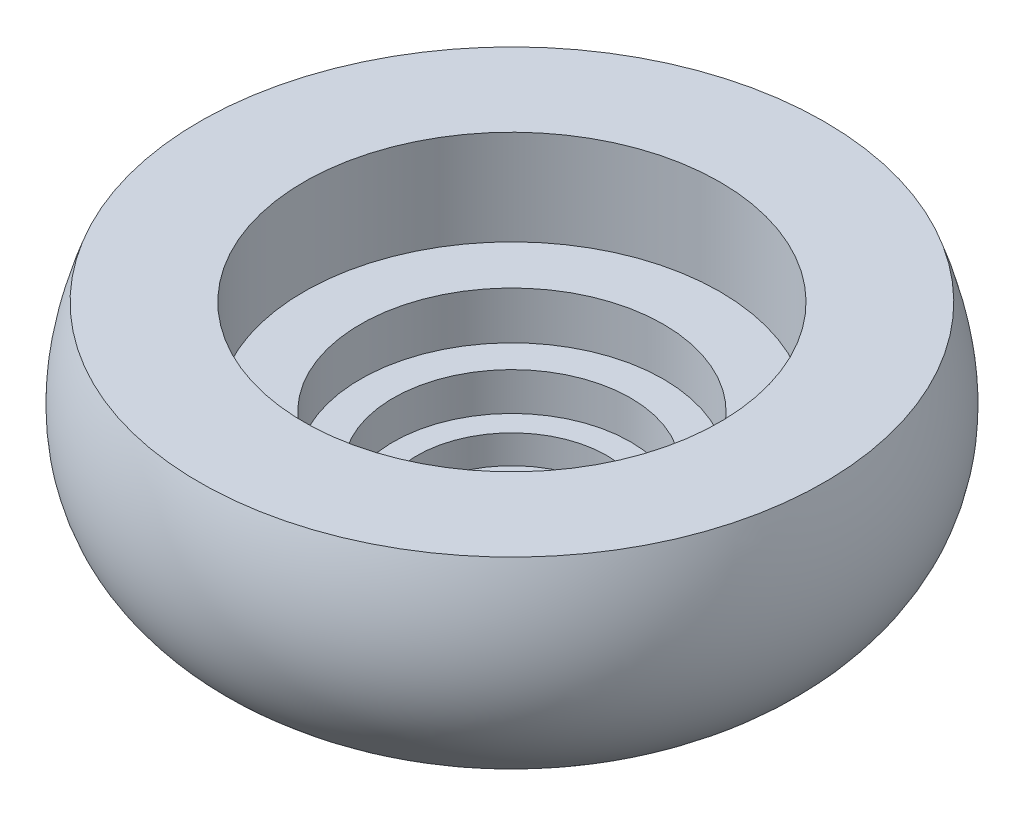
SolidWorks part; units mm, degrees
ref_plane "정면" through (0, 0, 0) normal (0, 0, 1) x (1, 0, 0)
ref_plane "윗면" through (0, 0, 0) normal (0, 1, 0) x (1, 0, 0)
ref_plane "우측면" through (0, 0, 0) normal (1, 0, 0) x (0, 0, -1)
sketch "스케치2" plane through (0, 0, 0) normal (0, 0, 1) x (1, 0, 0)
  line L0 (0, 0) -> (39.9375, 0) construction
  line L1 (39.9375, 0) -> (-43.125, 0) construction
  line L2 (0, 0) -> (0, 23.4063) construction
  line L3 (0, 23.4063) -> (0, -23.2813) construction
  line L4 (0, 0) -> (-5, 0)
  line L5 (-21.9, 30) -> (-32.9, 30)
  line L6 (-21.9, 30) -> (-21.9, 20)
  line L7 (-21.9, 20) -> (-15.95, 20)
  line L8 (-15.95, 20) -> (-15.95, 15)
  line L9 (-15.95, 15) -> (-12.5, 15)
  line L10 (-12.5, 15) -> (-12.5, 11)
  line L11 (-12.5, 11) -> (-10, 11)
  line L12 (-10, 11) -> (-10, 8)
  line L13 (-10, 8) -> (0, 8)
  line L14 (0, 0) -> (0, 8)
  line L15 (0, 8) -> (0, 0)
  circle A0 centre (0, 41) radius 48.4214
  spline S0 degree 3 poles (-5, 0) (-19.4224, 1.1158) (-41.1148, 7.0449) (-32.9, 30) knots 0 0 0 0 1 1 1 1
  point P8 (0, 41)
  point P25 (-33, 20)
  dimension "D1" = 5
  dimension "D2" = 21.9
  dimension "D3" = 15.95
  dimension "D4" = 12.5
  dimension "D5" = 10
  dimension "D6" = 10
  dimension "D7" = 5
  dimension "D8" = 4
  dimension "D9" = 3
  dimension "D10" = 8
  dimension "D11" = 41
  dimension "D12" = 3
  dimension "D13" = 15
  dimension "D14" = 3.5
  dimension "D15" = 7
  dimension "D16" = 6
  dimension "D17" = 13.5
  dimension "D18" = 11
revolve "회전2" add sketch "스케치2" angle 360 about L2
